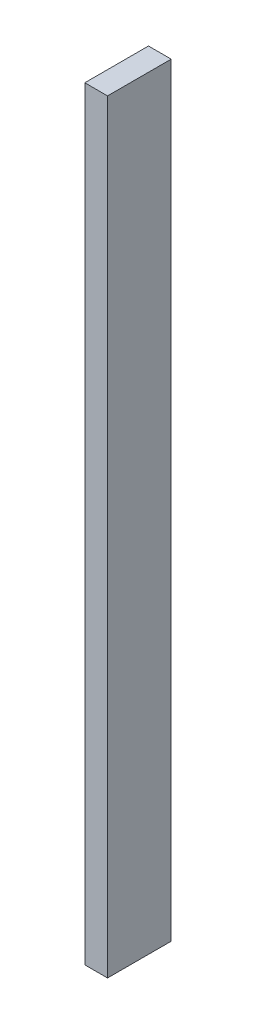
SolidWorks part; units mm, degrees
ref_plane "Front Plane" through (0, 0, 0) normal (0, 0, 1) x (1, 0, 0)
ref_plane "Top Plane" through (0, 0, 0) normal (0, 1, 0) x (1, 0, 0)
ref_plane "Right Plane" through (0, 0, 0) normal (1, 0, 0) x (0, 0, -1)
sketch "Sketch1" plane through (0, 0, 0) normal (0, 1, 0) x (1, 0, 0)
  line L1 (0, 0) -> (3.175, 0)
  line L2 (0, 0) -> (0, 8.89)
  line L3 (0, 8.89) -> (3.175, 8.89)
  line L4 (3.175, 0) -> (3.175, 8.89)
  dimension "D1" = 3.175
  dimension "D2" = 8.89
extrude "Boss-Extrude1" add sketch "Sketch1" along normal blind 106.68
equation "\"D1@Sketch1\"=1/8"
